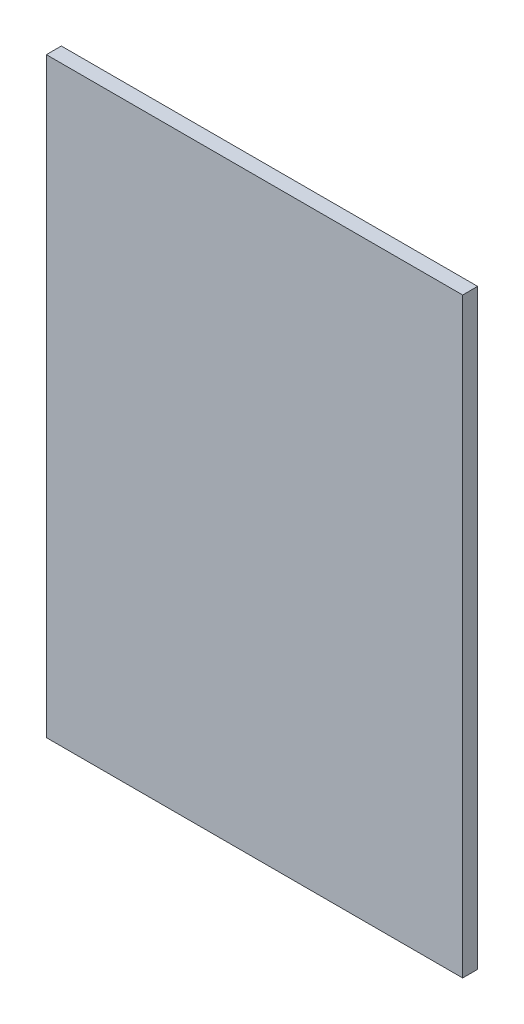
SolidWorks part; units mm, degrees
ref_plane "Alzado" through (0, 0, 0) normal (0, 0, 1) x (1, 0, 0)
ref_plane "Planta" through (0, 0, 0) normal (0, 1, 0) x (1, 0, 0)
ref_plane "Vista lateral" through (0, 0, 0) normal (1, 0, 0) x (0, 0, -1)
sketch "Croquis1" plane through (0, 0, 0) normal (0, 0, 1) x (1, 0, 0)
  line L1 (-69.5, -98.75) -> (69.5, -98.75)
  line L2 (-69.5, -98.75) -> (-69.5, 98.75)
  line L3 (-69.5, 98.75) -> (69.5, 98.75)
  line L4 (69.5, -98.75) -> (69.5, 98.75)
  line L5 (-69.5, -98.75) -> (69.5, 98.75) construction
  line L6 (-69.5, 98.75) -> (69.5, -98.75) construction
  point P0 (0, 0)
  dimension "D1" = 139
  dimension "D2" = 197.5
extrude "Saliente-Extruir1" add sketch "Croquis1" along normal blind 5
